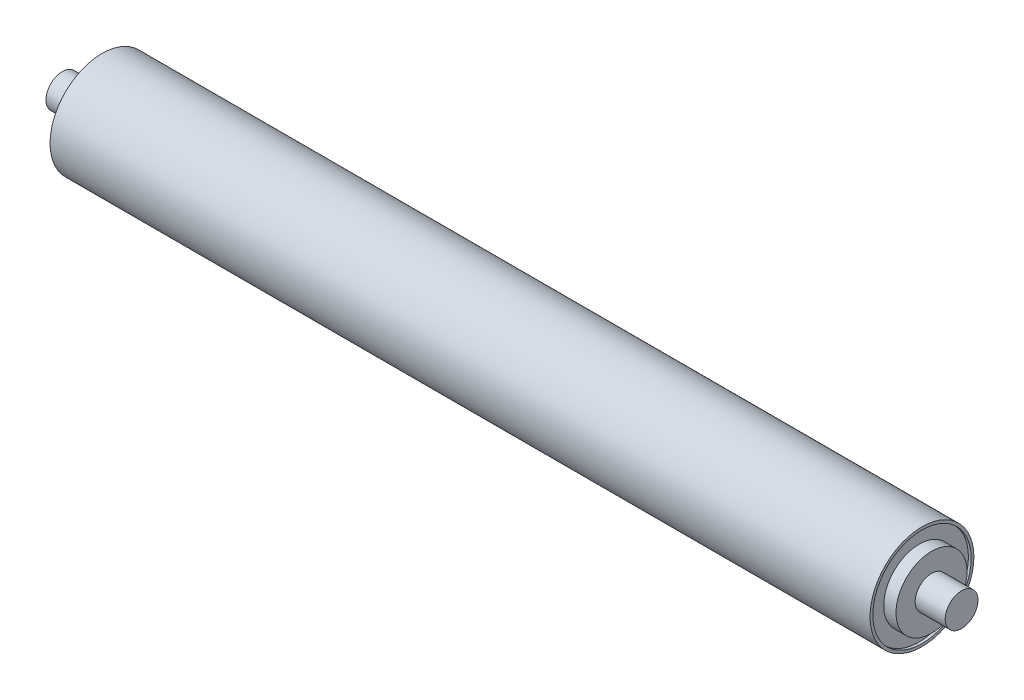
SolidWorks part; units mm, degrees
ref_plane "前视基准面" through (0, 0, 0) normal (0, 0, 1) x (1, 0, 0)
ref_plane "上视基准面" through (0, 0, 0) normal (0, 1, 0) x (1, 0, 0)
ref_plane "右视基准面" through (0, 0, 0) normal (1, 0, 0) x (0, 0, -1)
sketch "草图1" plane through (0, 0, 0) normal (0, 0, 1) x (1, 0, 0)
  line B0 (0, 0) -> (0, 6)
  line B1 (0, 6) -> (11, 6)
  line B2 (11, 6) -> (11, 13)
  line B3 (329, 0) -> (0, 0)
  line B4 (14.5, 19) -> (314.5, 19)
  line B5 (329, 0) -> (329, 6)
  line B6 (329, 6) -> (318, 6)
  line B7 (318, 6) -> (318, 13)
  line B8 (314.5, 18) -> (314.5, 19)
  line B9 (318, 13) -> (313.5, 13)
  line B10 (313.5, 18) -> (314.5, 18)
  line B11 (313.5, 13) -> (313.5, 18)
  line B12 (14.5, 18) -> (14.5, 19)
  line B13 (11, 13) -> (15.5, 13)
  line B14 (15.5, 18) -> (14.5, 18)
  line B15 (15.5, 13) -> (15.5, 18)
sketch_block_instance "A$C48F14BEB-1"
sketch_block "A$C48F14BEB"
revolve "旋转1" add sketch "草图1" angle 360 about L3
